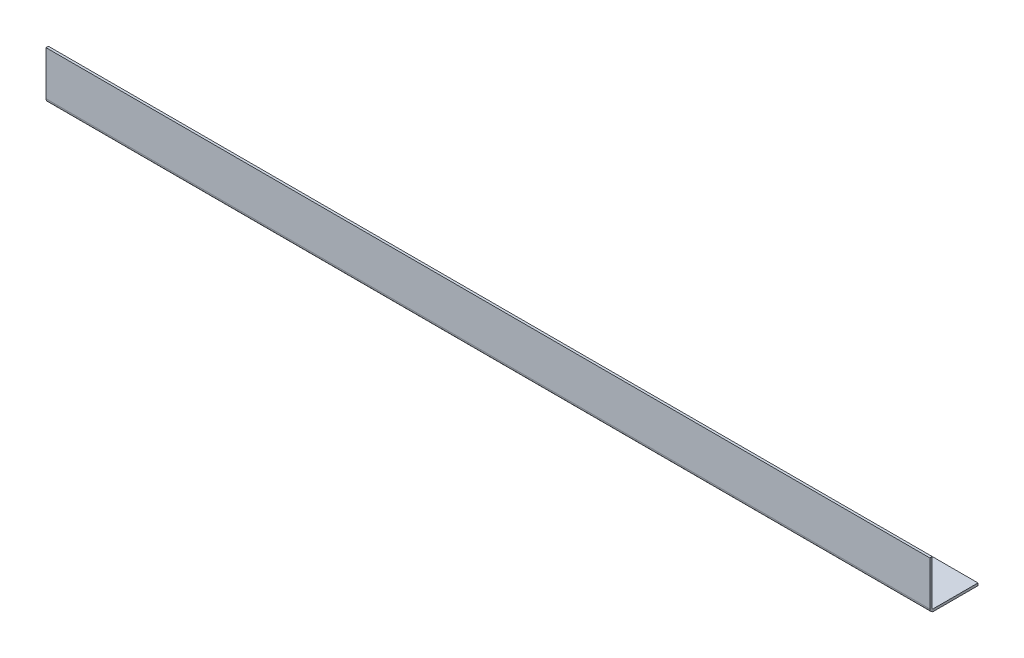
SolidWorks part; units mm, degrees
material "201 Annealed Stainless Steel (SS)"
ref_plane "Front Plane" through (0, 0, 0) normal (0, 0, 1) x (1, 0, 0)
ref_plane "Top Plane" through (0, 0, 0) normal (0, 1, 0) x (1, 0, 0)
ref_plane "Right Plane" through (0, 0, 0) normal (1, 0, 0) x (0, 0, -1)
sketch "Sketch1" plane through (0, 0, 0) normal (1, 0, 0) x (0, 0, -1)
  line L0 (0, 0) -> (0, 60)
  line L1 (0, 0) -> (60, 0)
  line L2 (60, 0) -> (60, 3)
  line L3 (60, 3) -> (3, 3)
  line L4 (3, 3) -> (3, 60)
  line L5 (3, 60) -> (0, 60)
  dimension "D1" = 60
  dimension "D2" = 60
  dimension "D3" = 3
extrude "Boss-Extrude1" add sketch "Sketch1" along normal mid plane 1100
fillet "Fillet1" radius 5 1 edges at (0, 0, 0)
fillet "Fillet2" radius 1 1 edges at (0, 3, -3)
